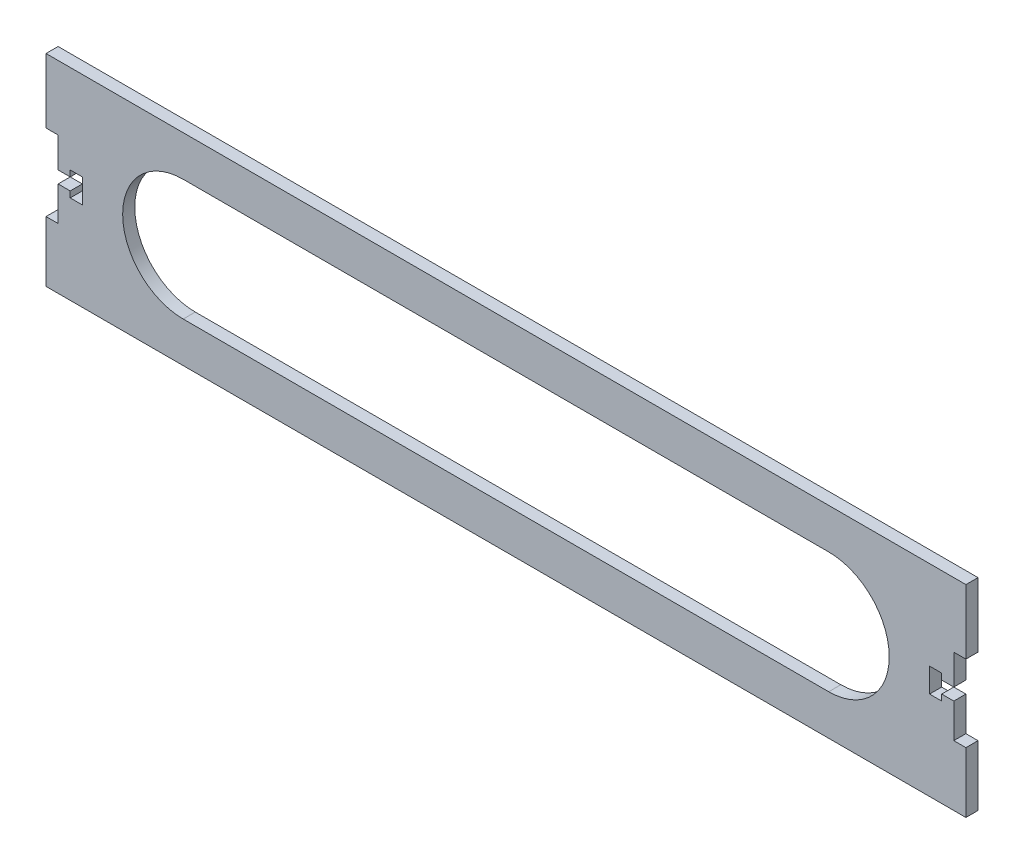
SolidWorks part; units mm, degrees
ref_plane "Alzado" through (0, 0, 0) normal (0, 0, 1) x (1, 0, 0)
ref_plane "Planta" through (0, 0, 0) normal (0, 1, 0) x (1, 0, 0)
ref_plane "Vista lateral" through (0, 0, 0) normal (1, 0, 0) x (0, 0, -1)
sketch "Croquis1" plane through (0, 0, 0) normal (0, 0, 1) x (1, 0, 0)
  line L0 (80, 0) -> (-80, 0) construction
  line L1 (111, -25) -> (-111, -25)
  line L2 (111, -25) -> (111, -1.5)
  line L3 (111, 25) -> (-111, 25)
  line L4 (-111, -25) -> (-111, -1.5)
  line L5 (111, -25) -> (-111, 25) construction
  line L6 (111, 25) -> (-111, -25) construction
  line L7 (80, -15) -> (-80, -15)
  line L8 (80, 15) -> (-80, 15)
  line L9 (-111, 0) -> (-105, 0) construction
  line L10 (-111, 1.5) -> (-108, 1.5)
  line L11 (-108, 1.5) -> (-108, 3)
  line L12 (-108, 3) -> (-105, 3)
  line L13 (-105, 3) -> (-105, -3)
  line L14 (-108, -3) -> (-105, -3)
  line L15 (-108, -1.5) -> (-108, -3)
  line L16 (-111, -1.5) -> (-108, -1.5)
  line L17 (-111, 1.5) -> (-111, 25)
  line L18 (0, 0) -> (0, 25) construction
  line L19 (111, 1.5) -> (108, 1.5)
  line L20 (108, 1.5) -> (108, 3)
  line L21 (108, 3) -> (105, 3)
  line L22 (105, 3) -> (105, -3)
  line L23 (108, -3) -> (105, -3)
  line L24 (108, -1.5) -> (108, -3)
  line L25 (111, -1.5) -> (108, -1.5)
  line L26 (111, 1.5) -> (111, 25)
  arc A0 (80, -15) -> (80, 15) centre (80, 0) ccw
  arc A1 (-80, 15) -> (-80, -15) centre (-80, 0) ccw
  point P0 (0, 0)
  point P8 (0, 0)
  point P13 (-95, 0)
  dimension "D1" = 222
  dimension "D2" = 50
  dimension "D3" = 30
  dimension "D4" = 16
  dimension "D5" = 6
  dimension "D6" = 1.5
  dimension "D7" = 3
  dimension "D8" = 3
extrude "Saliente-Extruir1" add sketch "Croquis1" along normal blind 3
sketch "Croquis2" plane through (-111, 0, 0) normal (-1, 0, 0) x (0, 0, 1)
  line L0 (3, 25) -> (3, 9) construction
  line L1 (3, 25) -> (3, 1.5) construction
  line L2 (-0.25, 9) -> (3.25, 9) construction
  line L3 (3, 17) -> (0, 17) construction
  line L4 (0, 25) -> (0, 1.5) construction
  line L5 (0, -25) -> (0, -10) construction
  line L6 (0, 9) -> (3, 9)
  line L7 (0, 9) -> (0, 25)
  line L8 (0, 25) -> (3, 25)
  line L9 (3, 9) -> (3, 25)
  line L10 (0, 9) -> (3, 25) construction
  line L11 (0, 25) -> (3, 9) construction
  line L12 (0, -1.5) -> (0, -25) construction
  line L15 (3.25, -10) -> (-0.25, -10) construction
  line L16 (0, -17.5) -> (3, -17.5) construction
  line L17 (3, -1.5) -> (3, -25) construction
  line L19 (3, -25) -> (0, -25)
  line L20 (3, -25) -> (3, -10)
  line L21 (3, -10) -> (0, -10)
  line L22 (0, -25) -> (0, -10)
  line L23 (3, -25) -> (0, -10) construction
  line L24 (3, -10) -> (0, -25) construction
  point P11 (1.5, 17)
  point P19 (1.5, -17.5)
extrude "Saliente-Extruir2" add sketch "Croquis2" along normal blind 3
mirror "Simetría1" about plane through (0, 0, 0) normal (1, 0, 0) of "Saliente-Extruir2"
